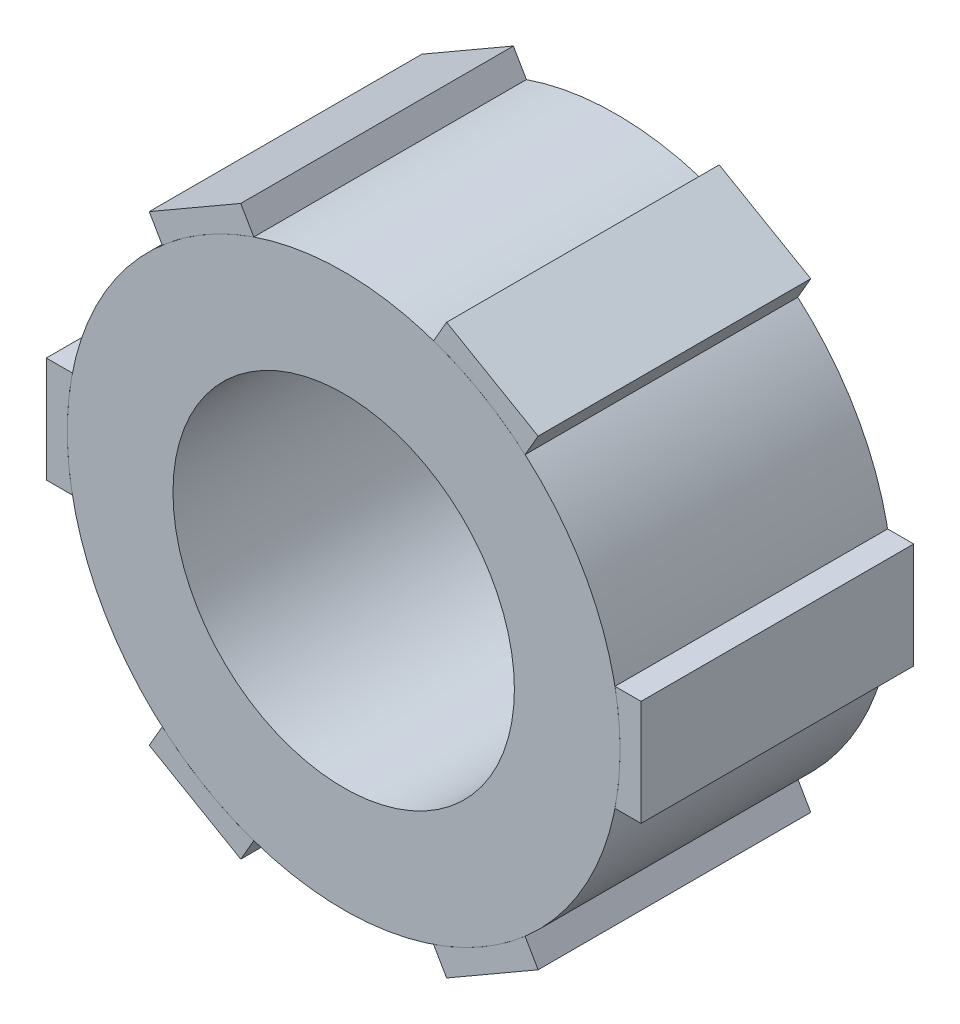
SolidWorks part; units mm, degrees
ref_plane "Front" through (0, 0, 0) normal (0, 0, 1) x (1, 0, 0)
ref_plane "Top" through (0, 0, 0) normal (0, 1, 0) x (1, 0, 0)
ref_plane "Right" through (0, 0, 0) normal (1, 0, 0) x (0, 0, -1)
sketch "Sketch1" plane through (0, 0, 0) normal (0, 0, 1) x (1, 0, 0)
  circle A0 centre (0, 0) radius 4.765
  circle A1 centre (0, 0) radius 7.715
  dimension "D1" = 2.95
  dimension "D2" = 9.53
extrude "Boss-Extrude1" add sketch "Sketch1" along normal blind 7.61
sketch "Sketch3" plane through (0, 0, 7.61) normal (0, 0, 1) x (1, 0, 0)
  line L0 (-2.8726, 7.9255) -> (-5.4274, 6.4505)
  line L1 (-8.3, 1.475) -> (8.3, 1.475)
  line L2 (-8.3, 1.475) -> (-8.3, -1.475)
  line L3 (-8.3, -1.475) -> (8.3, -1.475)
  line L4 (8.3, 1.475) -> (8.3, -1.475)
  line L5 (-8.3, 1.475) -> (8.3, -1.475) construction
  line L6 (-8.3, -1.475) -> (8.3, 1.475) construction
  line L7 (-2.8726, 7.9255) -> (5.4274, -6.4505)
  line L8 (5.4274, -6.4505) -> (2.8726, -7.9255)
  line L9 (-5.4274, 6.4505) -> (2.8726, -7.9255)
  line L10 (5.4274, 6.4505) -> (2.8726, 7.9255)
  line L11 (5.4274, 6.4505) -> (-2.8726, -7.9255)
  line L12 (-2.8726, -7.9255) -> (-5.4274, -6.4505)
  line L13 (2.8726, 7.9255) -> (-5.4274, -6.4505)
  line L14 (8.3, -1.475) -> (8.3, 1.475)
  line L15 (8.3, -1.475) -> (-8.3, -1.475)
  line L16 (-8.3, -1.475) -> (-8.3, 1.475)
  line L17 (8.3, 1.475) -> (-8.3, 1.475)
  point P0 (0, 0)
  circle M13 centre (0, 0) radius 7.715
  dimension "D1" = 16.6
  dimension "D3" = 2.95
  dimension "D2" = 4
extrude "Boss-Extrude3" add sketch "Sketch3" against normal up to surface (7.61 mm away) separate body contours L2 L3 L1 M13 | L0 L9 L7 M13 | L10 L13 L11 M13 | L4 L1 L3 M13 | L9 L8 L7 M13 | L13 L12 L11 M13 up to face at (7.715, 0, 0)
